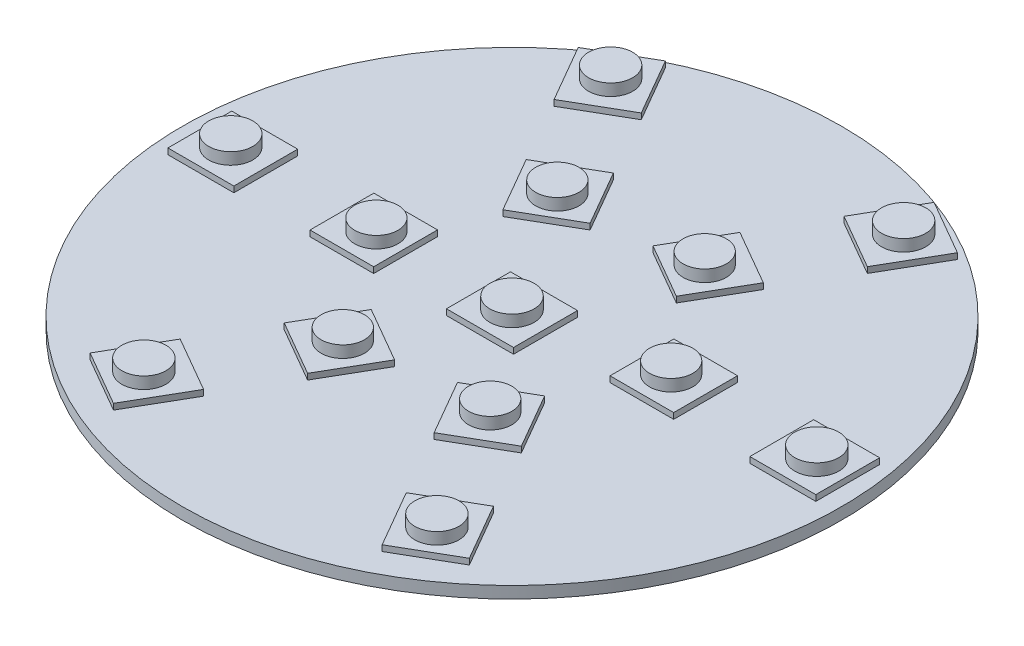
SolidWorks part; units mm, degrees
material "Water"
ref_plane "Front Plane" through (0, 0, 0) normal (0, 0, 1) x (1, 0, 0)
ref_plane "Top Plane" through (0, 0, 0) normal (0, 1, 0) x (1, 0, 0)
ref_plane "Right Plane" through (0, 0, 0) normal (1, 0, 0) x (0, 0, -1)
sketch "Sketch1" plane through (0, 0, 0) normal (0, 1, 0) x (1, 0, 0)
  circle A0 centre (0, 0) radius 28
extrude "Boss-Extrude1" add sketch "Sketch1" along normal blind 1
sketch "Sketch2" plane through (0, 1, 0) normal (0, 1, 0) x (1, 0, 0)
  line L0 (-8.9805, 19.9637) -> (-13.6777, 17.2517)
  line L1 (-26.5154, 2.7045) -> (-20.9132, 2.7045)
  line L2 (-26.5154, 2.7045) -> (-26.5154, -2.7194)
  line L3 (-26.5154, -2.7194) -> (-20.9132, -2.7194)
  line L4 (-20.9132, 2.7045) -> (-20.9132, -2.7194)
  line L5 (-26.5154, 2.7045) -> (-20.9132, -2.7194) construction
  line L6 (-26.5154, -2.7194) -> (-20.9132, 2.7045) construction
  line L7 (-14.4418, 2.7045) -> (-9.0328, 2.7045)
  line L8 (-14.4418, 2.7045) -> (-14.4418, -2.7194)
  line L9 (-14.4418, -2.7194) -> (-9.0328, -2.7194)
  line L10 (-9.0328, 2.7045) -> (-9.0328, -2.7194)
  line L11 (-14.4418, 2.7045) -> (-9.0328, -2.7194) construction
  line L12 (-14.4418, -2.7194) -> (-9.0328, 2.7045) construction
  line L13 (-2.8477, 2.7194) -> (2.8477, 2.7194)
  line L14 (-2.8477, 2.7194) -> (-2.8477, -2.7194)
  line L15 (-2.8477, -2.7194) -> (2.8477, -2.7194)
  line L16 (2.8477, 2.7194) -> (2.8477, -2.7194)
  line L17 (-2.8477, 2.7194) -> (2.8477, -2.7194) construction
  line L18 (-2.8477, -2.7194) -> (2.8477, 2.7194) construction
  line L19 (-11.7816, 24.8153) -> (-8.9805, 19.9637)
  line L20 (-11.7816, 24.8153) -> (-16.4788, 22.1034)
  line L21 (-16.4788, 22.1034) -> (-13.6777, 17.2517)
  line L22 (-10.4419, 11.6473) -> (-7.7374, 6.9629)
  line L23 (-5.7447, 14.3592) -> (-10.4419, 11.6473)
  line L24 (-5.7447, 14.3592) -> (-3.0402, 9.6749)
  line L25 (-3.0402, 9.6749) -> (-7.7374, 6.9629)
  line L26 (11.9328, 18.2592) -> (7.2356, 20.9711)
  line L27 (14.7339, 23.1108) -> (11.9328, 18.2592)
  line L28 (14.7339, 23.1108) -> (10.0367, 25.8227)
  line L29 (10.0367, 25.8227) -> (7.2356, 20.9711)
  line L30 (3.9998, 15.3666) -> (1.2953, 10.6823)
  line L31 (8.697, 12.6547) -> (3.9998, 15.3666)
  line L32 (8.697, 12.6547) -> (5.9925, 7.9704)
  line L33 (5.9925, 7.9704) -> (1.2953, 10.6823)
  line L34 (20.9132, -0.7045) -> (20.9132, 4.7194)
  line L35 (26.5154, -0.7045) -> (20.9132, -0.7045)
  line L36 (26.5154, -0.7045) -> (26.5154, 4.7194)
  line L37 (26.5154, 4.7194) -> (20.9132, 4.7194)
  line L38 (14.4418, 4.7194) -> (9.0328, 4.7194)
  line L39 (14.4418, -0.7045) -> (14.4418, 4.7194)
  line L40 (14.4418, -0.7045) -> (9.0328, -0.7045)
  line L41 (9.0328, -0.7045) -> (9.0328, 4.7194)
  line L42 (8.9805, -17.9637) -> (13.6777, -15.2517)
  line L43 (11.7816, -22.8153) -> (8.9805, -17.9637)
  line L44 (11.7816, -22.8153) -> (16.4788, -20.1034)
  line L45 (16.4788, -20.1034) -> (13.6777, -15.2517)
  line L46 (10.4419, -9.6473) -> (7.7374, -4.9629)
  line L47 (5.7447, -12.3592) -> (10.4419, -9.6473)
  line L48 (5.7447, -12.3592) -> (3.0402, -7.6749)
  line L49 (3.0402, -7.6749) -> (7.7374, -4.9629)
  line L50 (-11.9328, -16.2592) -> (-7.2356, -18.9711)
  line L51 (-14.7339, -21.1108) -> (-11.9328, -16.2592)
  line L52 (-14.7339, -21.1108) -> (-10.0367, -23.8227)
  line L53 (-10.0367, -23.8227) -> (-7.2356, -18.9711)
  line L54 (-3.9998, -13.3666) -> (-1.2953, -8.6823)
  line L55 (-8.697, -10.6547) -> (-3.9998, -13.3666)
  line L56 (-8.697, -10.6547) -> (-5.9925, -5.9704)
  line L57 (-5.9925, -5.9704) -> (-1.2953, -8.6823)
  point P0 (-23.7143, -0.0074)
  point P5 (-11.7373, -0.0074)
  point P10 (0, 0)
  point P58 (0, 1)
  dimension "D1" = 6
extrude "Boss-Extrude3" add sketch "Sketch2" along normal blind 0.5
sketch "Sketch3" plane through (0, 1.5, 0) normal (0, 1, 0) x (1, 0, 0)
  circle A0 centre (-23.8954, 0) radius 1.876
  circle A1 centre (-11.5232, 0) radius 1.8415
  circle A2 centre (0, 0) radius 1.8806
  circle A3 centre (-12.8137, 21.194) radius 1.876
  circle A4 centre (-6.6276, 10.4794) radius 1.8415
  circle A5 centre (11.0817, 22.194) radius 1.876
  circle A6 centre (4.8956, 11.4794) radius 1.8415
  circle A7 centre (23.8954, 2) radius 1.876
  circle A8 centre (11.5232, 2) radius 1.8415
  circle A9 centre (12.8137, -19.194) radius 1.876
  circle A10 centre (6.6276, -8.4794) radius 1.8415
  circle A11 centre (-11.0817, -20.194) radius 1.876
  circle A12 centre (-4.8956, -9.4794) radius 1.8415
  point P29 (0, 1)
  dimension "D1" = 6
extrude "Boss-Extrude4" add sketch "Sketch3" along normal blind 1
